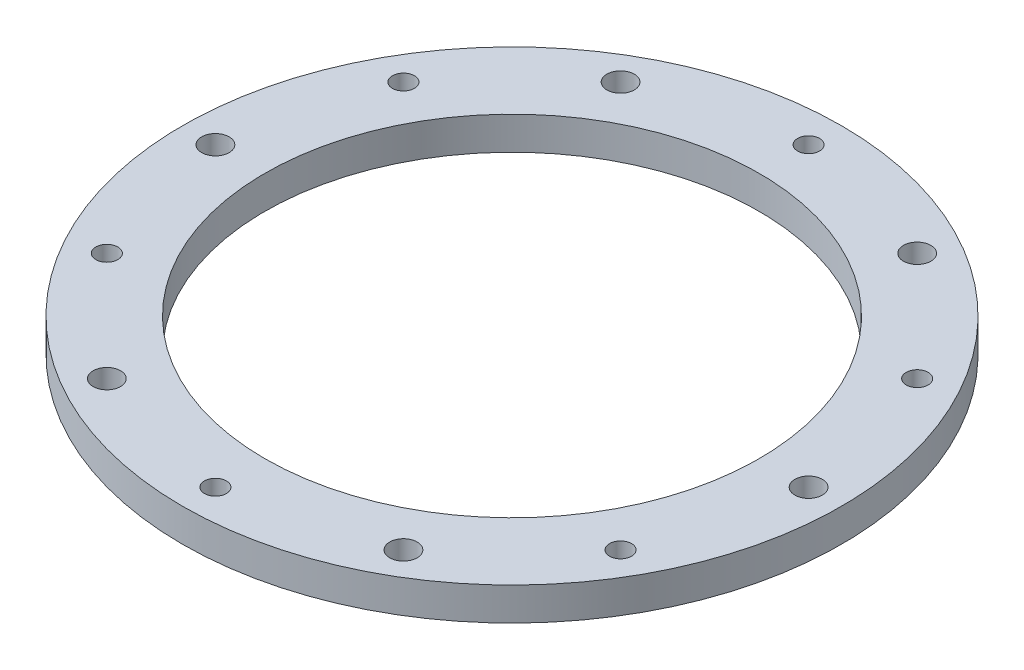
SolidWorks part; units mm, degrees
ref_plane "Front Plane" through (0, 0, 0) normal (0, 0, 1) x (1, 0, 0)
ref_plane "Top Plane" through (0, 0, 0) normal (0, 1, 0) x (1, 0, 0)
ref_plane "Right Plane" through (0, 0, 0) normal (1, 0, 0) x (0, 0, -1)
sketch "Sketch1" plane through (0, 0, 0) normal (0, 1, 0) x (1, 0, 0)
  circle A0 centre (0, 0) radius 30
  circle A1 centre (0, 0) radius 27 construction
  circle A2 centre (0, 27) radius 1
  circle A3 centre (23.3827, 13.5) radius 1
  circle A4 centre (23.3827, -13.5) radius 1
  circle A5 centre (0, -27) radius 1
  circle A6 centre (-23.3827, -13.5) radius 1
  circle A7 centre (-23.3827, 13.5) radius 1
  circle A8 centre (0, 0) radius 22.5
  point P18 (0, 0)
  dimension "D1" = 60
  dimension "D2" = 54
  dimension "D3" = 2
  dimension "D5" = 45
  dimension "D4" = 6
extrude "Boss-Extrude1" add sketch "Sketch1" along normal blind 3
sketch "Sketch3" plane through (0, 3, 0) normal (0, 1, 0) x (1, 0, 0)
  line L0 (-13.5, 23.3827) -> (0, 0) construction
  line L1 (0, 0) -> (12.944, 0) construction
  circle A0 centre (0, 0) radius 27 construction
  circle A1 centre (-13.5, 23.3827) radius 1.25
  circle A2 centre (13.5, 23.3827) radius 1.25
  circle A3 centre (27, 0) radius 1.25
  circle A4 centre (13.5, -23.3827) radius 1.25
  circle A5 centre (-13.5, -23.3827) radius 1.25
  circle A6 centre (-27, 0) radius 1.25
  point P17 (0, 0)
  dimension "D1" = 54
  dimension "D2" = 2.5
  dimension "D4" = 120
  dimension "D3" = 6
extrude "Cut-Extrude1" cut sketch "Sketch3" against normal blind 3
